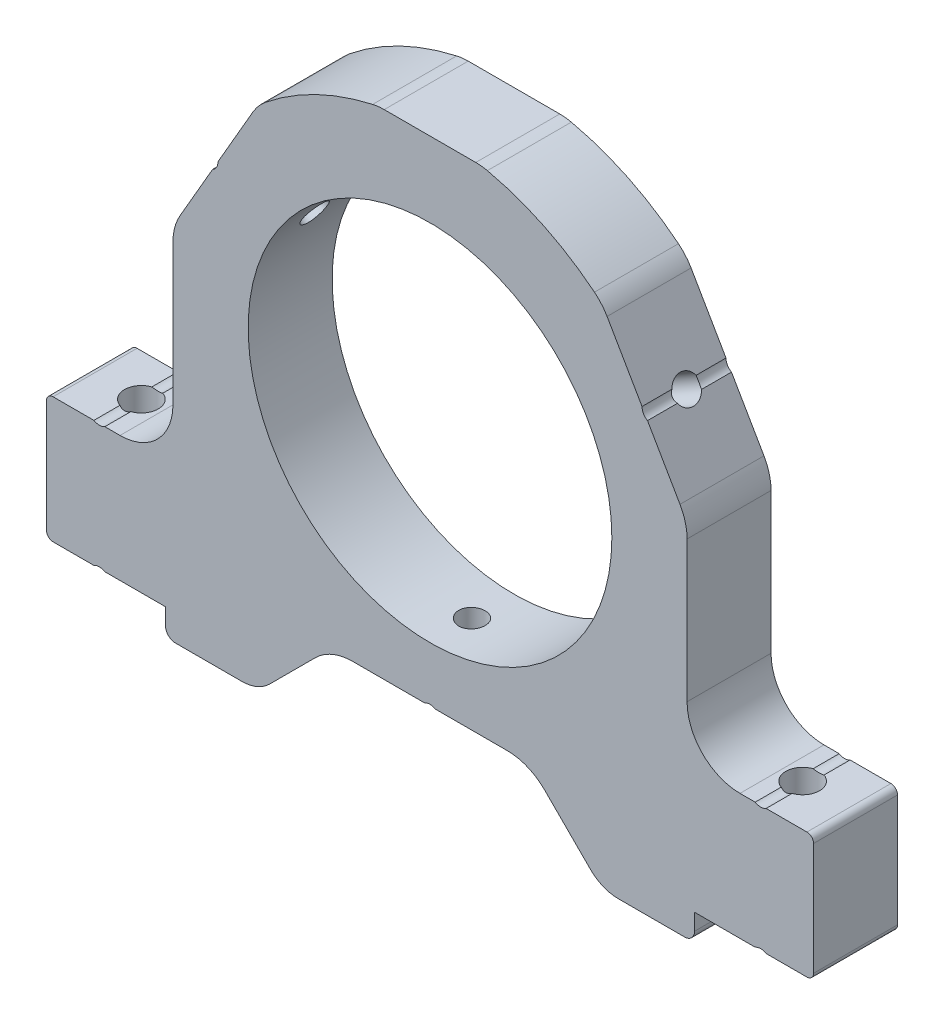
SolidWorks part; units mm, degrees
ref_plane "Front Plane" through (0, 0, 0) normal (0, 0, 1) x (1, 0, 0)
ref_plane "Top Plane" through (0, 0, 0) normal (0, 1, 0) x (1, 0, 0)
ref_plane "Right Plane" through (0, 0, 0) normal (1, 0, 0) x (0, 0, -1)
sketch "Sketch1" plane through (0, 0, 0) normal (0, 0, 1) x (1, 0, 0)
  line L36 (284.2365, 94.4174) -> (284.2365, 77.4174)
  line L37 (380.7365, 72.4174) -> (370.7218, 72.4174)
  line L38 (313.7512, 72.4174) -> (303.7365, 72.4174)
  line L39 (302.2365, 76.4174) -> (302.2365, 73.9174)
  line L40 (303.362, 124.7349) -> (303.362, 103.4174)
  line L41 (315.4568, 147.8273) -> (310.1736, 138.6765)
  line L42 (309.3474, 137.2456) -> (304.4338, 128.7349)
  line L43 (285.2365, 76.4174) -> (291.4103, 76.4174)
  line L44 (293.0627, 76.4174) -> (302.2365, 76.4174)
  line L45 (382.2365, 76.4174) -> (391.4103, 76.4174)
  line L46 (393.0627, 76.4174) -> (399.2365, 76.4174)
  line L47 (353.9228, 83.4174) -> (343.0627, 83.4174)
  line L48 (341.4103, 83.4174) -> (330.5502, 83.4174)
  line L49 (399.2365, 95.4174) -> (393.0627, 95.4174)
  line L50 (391.4103, 95.4174) -> (389.111, 95.4174)
  line L51 (285.2365, 95.4174) -> (291.4103, 95.4174)
  line L52 (293.0627, 95.4174) -> (295.362, 95.4174)
  line L53 (366.4791, 74.1747) -> (359.5796, 81.0742)
  line L54 (324.8933, 81.0742) -> (317.9938, 74.1747)
  line L55 (381.111, 124.7349) -> (381.111, 103.4174)
  line L56 (382.2365, 76.4174) -> (382.2365, 73.9174)
  line L57 (349.1596, 158.0674) -> (335.3134, 158.0674)
  line L58 (369.0161, 147.8273) -> (374.2993, 138.6765)
  line L59 (375.1255, 137.2456) -> (380.0392, 128.7349)
  line L60 (400.2365, 77.4174) -> (400.2365, 94.4174)
  arc A35 (333.562, 157.8733) -> (317.363, 150.0547) centre (342.2365, 119.2111) ccw
  arc A36 (367.1099, 150.0547) -> (350.9109, 157.8733) centre (342.2365, 119.2111) ccw
  circle A37 centre (342.2365, 119.2111) radius 27.5
  arc A38 (359.5796, 81.0742) -> (353.9228, 83.4174) centre (353.9228, 75.4174) ccw
  arc A39 (330.5502, 83.4174) -> (324.8933, 81.0742) centre (330.5502, 75.4174) ccw
  arc A40 (295.362, 95.4174) -> (303.362, 103.4174) centre (295.362, 103.4174) ccw
  arc A41 (381.111, 103.4174) -> (389.111, 95.4174) centre (389.111, 103.4174) ccw
  arc A42 (381.111, 124.7349) -> (380.0392, 128.7349) centre (373.111, 124.7349) ccw
  arc A43 (304.4338, 128.7349) -> (303.362, 124.7349) centre (311.362, 124.7349) ccw
  arc A44 (317.363, 150.0547) -> (315.4568, 147.8273) centre (322.385, 143.8273) ccw
  arc A45 (335.3134, 158.0674) -> (333.562, 157.8733) centre (335.3134, 150.0674) ccw
  arc A46 (350.9109, 157.8733) -> (349.1596, 158.0674) centre (349.1596, 150.0674) ccw
  arc A47 (369.0161, 147.8273) -> (367.1099, 150.0547) centre (362.0879, 143.8273) ccw
  arc A48 (366.4791, 74.1747) -> (370.7218, 72.4174) centre (370.7218, 78.4174) ccw
  arc A49 (313.7512, 72.4174) -> (317.9938, 74.1747) centre (313.7512, 78.4174) ccw
  arc A50 (309.3474, 137.2456) -> (310.1736, 138.6765) centre (308.5481, 138.6611) ccw
  arc A51 (374.2993, 138.6765) -> (375.1255, 137.2456) centre (375.9249, 138.6611) ccw
  arc A52 (393.0627, 76.4174) -> (391.4103, 76.4174) centre (392.2365, 75.0174) ccw
  arc A53 (391.4103, 95.4174) -> (393.0627, 95.4174) centre (392.2365, 96.8174) ccw
  arc A54 (343.0627, 83.4174) -> (341.4103, 83.4174) centre (342.2365, 82.0174) ccw
  arc A55 (293.0627, 76.4174) -> (291.4103, 76.4174) centre (292.2365, 75.0174) ccw
  arc A56 (291.4103, 95.4174) -> (293.0627, 95.4174) centre (292.2365, 96.8174) ccw
  arc A57 (380.7365, 72.4174) -> (382.2365, 73.9174) centre (380.7365, 73.9174) ccw
  arc A58 (302.2365, 73.9174) -> (303.7365, 72.4174) centre (303.7365, 73.9174) ccw
  arc A59 (399.2365, 76.4174) -> (400.2365, 77.4174) centre (399.2365, 77.4174) ccw
  arc A60 (400.2365, 94.4174) -> (399.2365, 95.4174) centre (399.2365, 94.4174) ccw
  arc A61 (284.2365, 77.4174) -> (285.2365, 76.4174) centre (285.2365, 77.4174) ccw
  arc A62 (285.2365, 95.4174) -> (284.2365, 94.4174) centre (285.2365, 94.4174) ccw
extrude "Boss-Extrude1" add sketch "Sketch1" along normal blind 12.7
sketch "Sketch2" plane through (0, 95.4174, 0) normal (0, 1, 0) x (1, 0, 0)
  line L0 (291.4103, -6.35) -> (293.0627, -6.35) construction
  line L1 (291.4103, -12.7) -> (291.4103, 0) construction
  line L2 (293.0627, -12.7) -> (293.0627, 0) construction
  line L3 (391.4103, -6.35) -> (393.0627, -6.35) construction
  line L4 (391.4103, -12.7) -> (391.4103, 0) construction
  line L5 (393.0627, -12.7) -> (393.0627, 0) construction
  circle A0 centre (292.2365, -6.35) radius 2.55
  circle A1 centre (392.2365, -6.35) radius 2.55
extrude "Cut-Extrude1" cut sketch "Sketch2" against normal through all
sketch "Sketch3" plane through (0, 83.4174, 0) normal (0, -1, 0) x (1, 0, 0)
  line L0 (341.4103, 6.35) -> (343.0627, 6.35) construction
  line L1 (341.4103, 12.7) -> (341.4103, 0) construction
  line L2 (343.0627, 12.7) -> (343.0627, 0) construction
  circle A0 centre (342.2365, 6.35) radius 2
sketch "Sketch4" plane through (172.5815, -99.64, 0) normal (-0.866, 0.5, 0) x (0, 0, 1)
  line L0 (6.35, 273.5319) -> (6.35, 275.1842) construction
  line L1 (12.7, 273.5319) -> (0, 273.5319) construction
  line L2 (12.7, 275.1842) -> (0, 275.1842) construction
  circle A0 centre (6.35, 274.358) radius 2
sketch "Sketch5" plane through (340.7732, 196.7455, 0) normal (0.866, 0.5, 0) x (0, 0, -1)
  line L0 (-6.35, -67.0523) -> (-6.35, -68.7046) construction
  line L1 (-12.7, -67.0523) -> (0, -67.0523) construction
  line L2 (-12.7, -68.7046) -> (0, -68.7046) construction
  circle A0 centre (-6.35, -67.8784) radius 2
extrude "Cut-Extrude2" cut sketch "Sketch4" against normal blind 15
extrude "Cut-Extrude3" cut sketch "Sketch5" against normal blind 15
extrude "Cut-Extrude4" cut sketch "Sketch3" against normal blind 15
